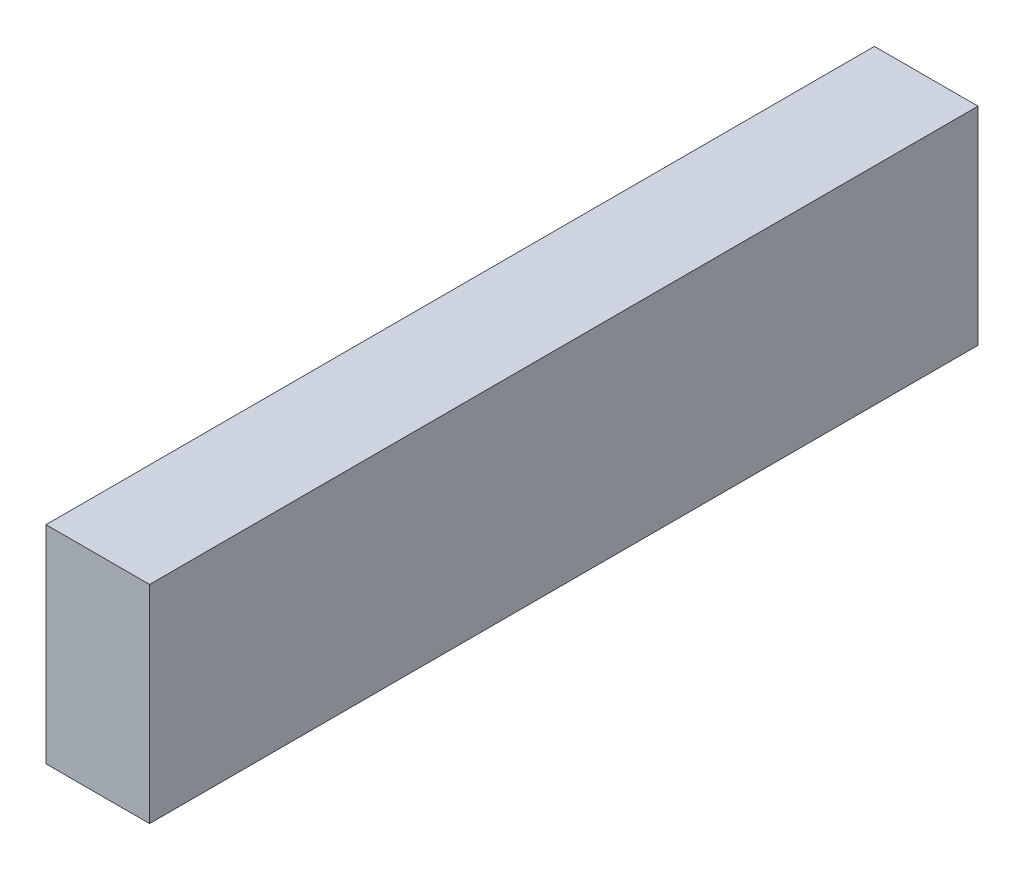
SolidWorks part; units mm, degrees
material "Plain Carbon Steel"
ref_plane "Front Plane" through (0, 0, 0) normal (0, 0, 1) x (1, 0, 0)
ref_plane "Top Plane" through (0, 0, 0) normal (0, 1, 0) x (1, 0, 0)
ref_plane "Right Plane" through (0, 0, 0) normal (1, 0, 0) x (0, 0, -1)
sketch "Sketch1" plane through (0, 0, 0) normal (0, 0, 1) x (1, 0, 0)
  line L1 (-3.175, -6.35) -> (3.175, -6.35)
  line L2 (-3.175, -6.35) -> (-3.175, 6.35)
  line L3 (-3.175, 6.35) -> (3.175, 6.35)
  line L4 (3.175, -6.35) -> (3.175, 6.35)
  line L5 (-3.175, -6.35) -> (3.175, 6.35) construction
  line L6 (-3.175, 6.35) -> (3.175, -6.35) construction
  point P0 (0, 0)
  dimension "D1" = 12.7
  dimension "D2" = 6.35
extrude "Extrude1" add sketch "Sketch1" along normal blind 50.8
